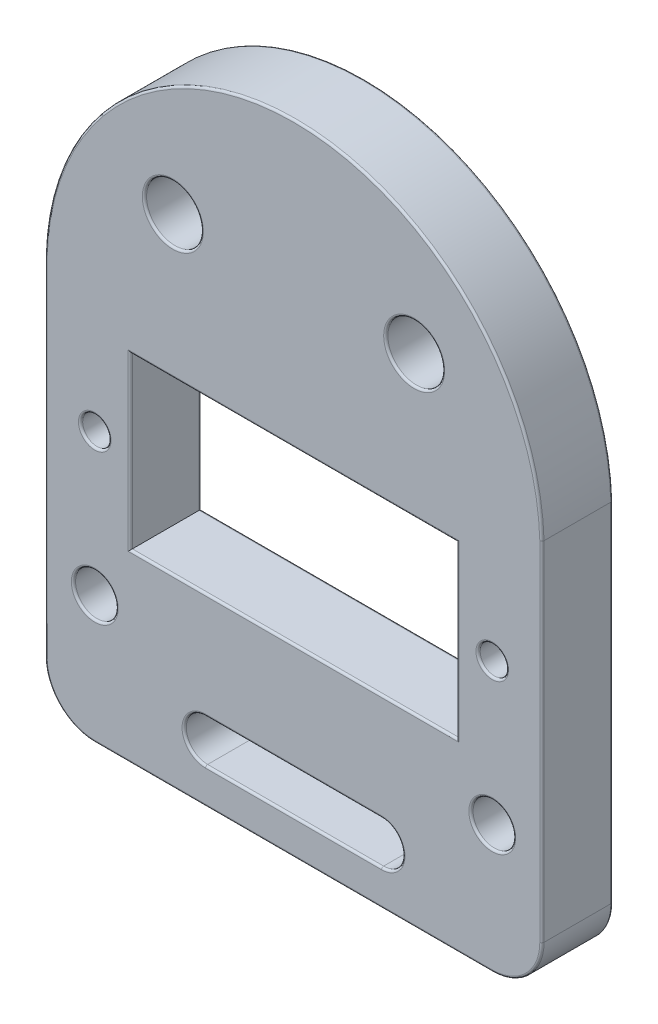
SolidWorks part; units mm, degrees
ref_plane "Front Plane" through (0, 0, 0) normal (0, 0, 1) x (1, 0, 0)
ref_plane "Top Plane" through (0, 0, 0) normal (0, 1, 0) x (1, 0, 0)
ref_plane "Right Plane" through (0, 0, 0) normal (1, 0, 0) x (0, 0, -1)
sketch "Sketch1" plane through (0, 0, 0) normal (0, 0, 1) x (1, 0, 0)
  line L0 (0, -19) -> (0, 26) construction
  line L1 (-11.5, -6) -> (11.5, -6)
  line L2 (-11.5, -6) -> (-11.5, 6)
  line L3 (-11.5, 6) -> (11.5, 6)
  line L4 (11.5, -6) -> (11.5, 6)
  line L5 (-11.5, -6) -> (11.5, 6) construction
  line L6 (-11.5, 6) -> (11.5, -6) construction
  line L7 (-6.2, -15) -> (6.2, -15) construction
  line L8 (-6.2, -13.5) -> (6.2, -13.5)
  line L9 (-6.2, -16.5) -> (6.2, -16.5)
  line L11 (-17.5, 9) -> (17.5, 9) construction
  line L12 (-17.5, 9) -> (-17.5, -19)
  line L13 (-17.5, -19) -> (17.5, -19)
  line L14 (17.5, 9) -> (17.5, -19)
  circle A0 centre (-14, 0) radius 1
  circle A1 centre (-14, -10) radius 1.5
  arc A2 (-6.2, -13.5) -> (-6.2, -16.5) centre (-6.2, -15) ccw
  arc A3 (6.2, -16.5) -> (6.2, -13.5) centre (6.2, -15) ccw
  circle A4 centre (-8.5, 16) radius 2
  circle A5 centre (14, -10) radius 1.5
  circle A6 centre (14, 0) radius 1
  circle A7 centre (8.5, 16) radius 2
  arc A8 (-17.5, 9) -> (17.5, 9) centre (0, 8.4926) cw
  point P0 (0, 0)
  point P13 (0, -15)
  point P26 (0, -19)
  dimension "D5" = 2
  dimension "D6" = 3
  dimension "D11" = 1.5
  dimension "D12" = 4
  dimension "D1" = 23
  dimension "D2" = 12
  dimension "D3" = 45
  dimension "D4" = 13
  dimension "D7" = 2.5
  dimension "D8" = 10
  dimension "D9" = 12.4
  dimension "D10" = 4
  dimension "D13" = 8.5
  dimension "D14" = 10
  dimension "D15" = 28
  dimension "D16" = 35
extrude "Boss-Extrude1" add sketch "Sketch1" along normal blind 5
fillet "Fillet1" radius 3.5 2 edges at (-17.5, -19, 2.5) (17.5, -19, 2.5)
fillet "Fillet2" radius 0.15 40 edges at (6.5, 16, 0) (12.5, -10, 0) (7.7, -15, 0) (0, -16.5, 0) (-7.7, -15, 0) (0, -13.5, 0) (-12.5, -10, 0) (-11.5, 0, 0) (0, 6, 0) (11.5, 0, 0) (0, -6, 0) (16.4749, -17.9749, 0) (17.5, -3.25, 0) (0, 26, 0) (-17.5, -3.25, 0) (-16.4749, -17.9749, 0) (0, -19, 0) (-13, 0, 0) (-6.5, 16, 0) (13, 0, 0) (6.5, 16, 5) (13, 0, 5) (12.5, -10, 5) (-6.5, 16, 5) (0, -16.5, 5) (7.7, -15, 5) (0, -13.5, 5) (-7.7, -15, 5) (0, 26, 5) (17.5, -3.25, 5) (16.4749, -17.9749, 5) (0, -19, 5) (-16.4749, -17.9749, 5) (-17.5, -3.25, 5) (0, 6, 5) (-11.5, 0, 5) (0, -6, 5) (11.5, 0, 5) (-13, 0, 5) (-12.5, -10, 5)
